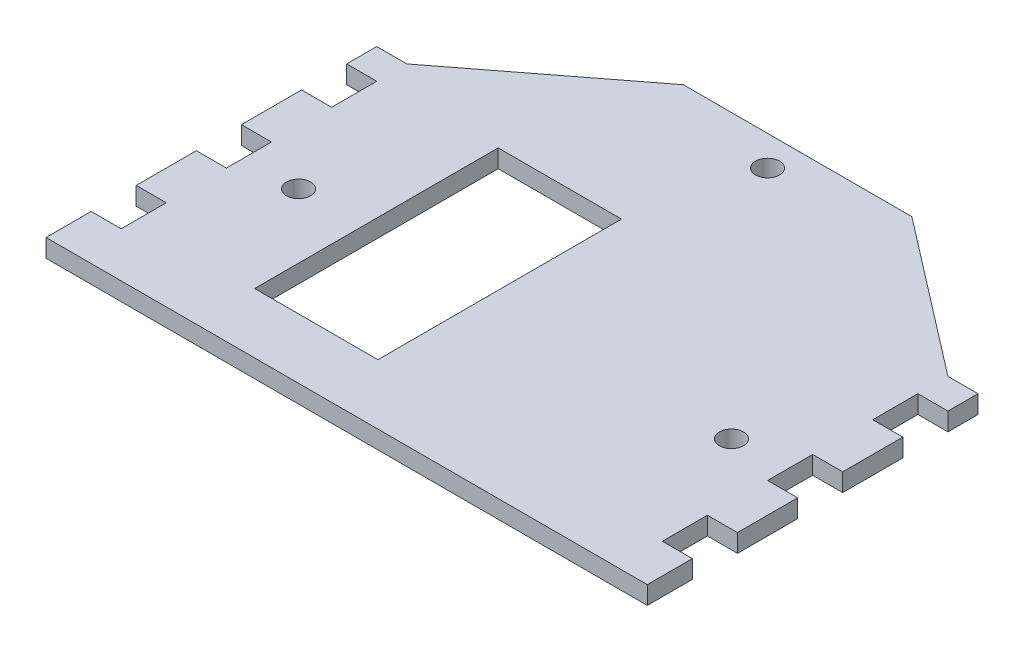
SolidWorks part; units mm, degrees
ref_plane "Front Plane" through (0, 0, 0) normal (0, 0, 1) x (1, 0, 0)
ref_plane "Top Plane" through (0, 0, 0) normal (0, 1, 0) x (1, 0, 0)
ref_plane "Right Plane" through (0, 0, 0) normal (1, 0, 0) x (0, 0, -1)
sketch "Sketch1" plane through (0, 0, 0) normal (0, 1, 0) x (1, 0, 0)
  line L0 (50, 0) -> (-50, 0) construction
  line L1 (0, 54.3862) -> (0, -40) construction
  line L2 (-45, 10) -> (-45, 2.5)
  line L3 (-50, -32.5) -> (-50, -40)
  line L4 (45, -15) -> (45, -7.5)
  line L5 (19, 35) -> (-19, 35)
  line L6 (-50, -40) -> (50, -40)
  line L7 (-50, 10) -> (-50, 15)
  line L8 (-50, 15) -> (-45, 15)
  line L9 (-19, 35) -> (-45, 15)
  line L10 (19, 35) -> (45, 15)
  line L11 (45, -32.5) -> (45, -25)
  line L13 (45, 15) -> (50, 15)
  line L15 (50, 15) -> (50, 10)
  line L18 (-50, 10) -> (-45, 10)
  line L19 (-25.3, 10.5) -> (-4.8, 10.5)
  line L20 (45, 2.5) -> (45, 10)
  line L22 (-50, -32.5) -> (-45, -32.5)
  line L23 (-45, -32.5) -> (-45, -25)
  line L24 (-50, -25) -> (-50, -15)
  line L25 (-45, -25) -> (-50, -25)
  line L26 (-45, -15) -> (-45, -7.5)
  line L27 (-50, -15) -> (-45, -15)
  line L28 (-50, -7.5) -> (-50, 2.5)
  line L29 (-45, -7.5) -> (-50, -7.5)
  line L30 (-50, 2.5) -> (-45, 2.5)
  line L32 (50, -32.5) -> (50, -40)
  line L33 (50, -32.5) -> (45, -32.5)
  line L34 (45, -25) -> (50, -25)
  line L35 (50, -25) -> (50, -15)
  line L36 (50, -15) -> (45, -15)
  line L37 (45, -7.5) -> (50, -7.5)
  line L38 (50, -7.5) -> (50, 2.5)
  line L39 (50, 2.5) -> (45, 2.5)
  line L40 (-4.8, 10.5) -> (-4.8, -30)
  line L41 (-4.8, -30) -> (-25.3, -30)
  line L43 (50, 10) -> (45, 10)
  line L44 (-25.3, -30) -> (-25.3, 10.5)
  circle A6 centre (0, 30) radius 2
  circle A8 centre (-36, -12) radius 2
  circle A9 centre (36, -12) radius 2
  point P1 (-50, 0)
  point P4 (0, 0)
  point P8 (14.819, 0)
  point P10 (0, 0)
  point P14 (0, 0)
  point P16 (-47.5, 2.5)
  point P25 (-45, 6.25)
  point P26 (0, 0)
  point P27 (0, 0)
  point P31 (0, 0)
  point P33 (0, 0)
  point P34 (-19, 35)
  point P35 (0, 0)
  point P36 (0, 0)
  point P37 (32.5187, -40)
  point P38 (32.7011, -40)
  point P39 (0, 0)
  point P40 (0, 0)
  point P41 (0, -40)
  point P59 (-47.5, -15)
  point P62 (-47.5, -7.5)
  point P71 (0, 0)
  point P72 (36, -12)
  point P73 (51.1178, -40)
  point P74 (50.4087, -40)
  point P75 (0, 0)
  point P76 (37.1132, -40)
  point P77 (-51.3464, -40)
  dimension "D5" = 36
  dimension "D6" = 40.5
  dimension "D7" = 20.5
  dimension "D8" = 10
  dimension "D9" = 19.7
  dimension "D11" = 5
  dimension "D13" = 5
  dimension "D16" = 12
  dimension "D10" = 4
  dimension "D1" = 35
  dimension "D3" = 7.5
  dimension "D4" = 45
  dimension "D12" = 5
  dimension "D15" = 38
  dimension "D17" = 7.5
  dimension "D18" = 40
  dimension "D19" = 7.5
  dimension "D20" = 5
  dimension "D21" = 10
  dimension "D22" = 7.5
  dimension "D23" = 10
extrude "Boss-Extrude1" add sketch "Sketch1" along normal blind 3
